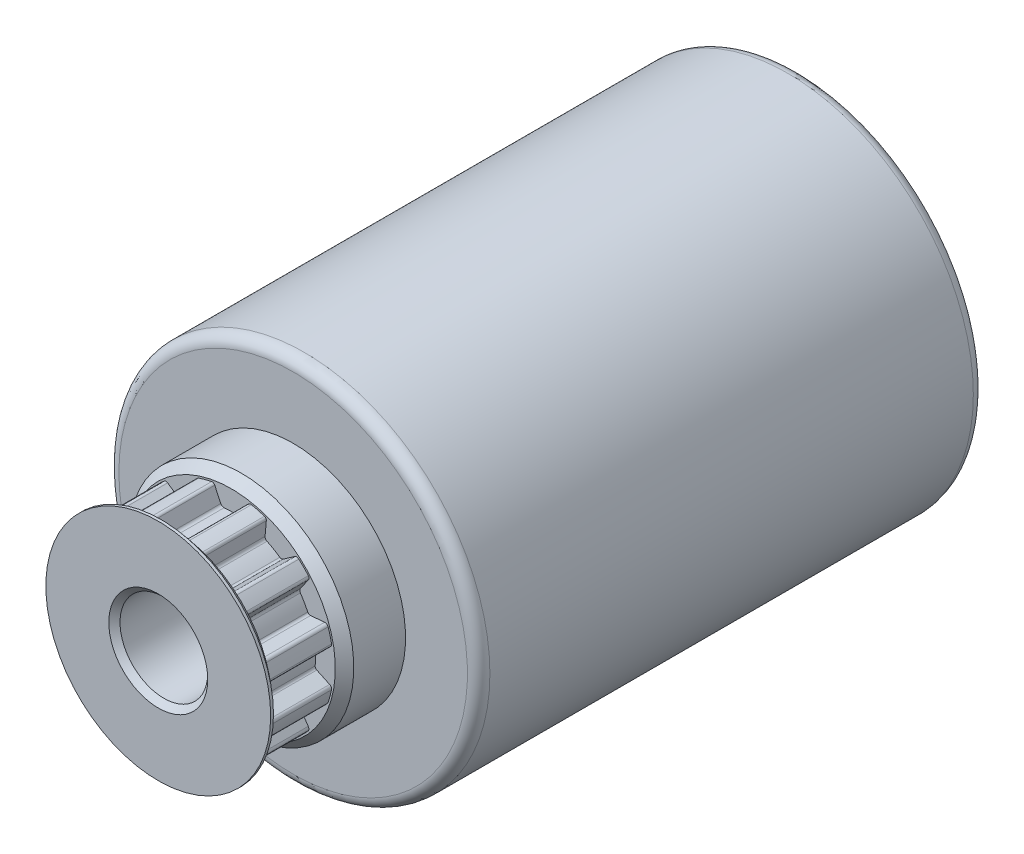
SolidWorks part; units mm, degrees
ref_plane "정면" through (0, 0, 0) normal (0, 0, 1) x (1, 0, 0)
ref_plane "윗면" through (0, 0, 0) normal (0, 1, 0) x (1, 0, 0)
ref_plane "우측면" through (0, 0, 0) normal (1, 0, 0) x (0, 0, -1)
sketch "스케치1" plane through (0, 0, 0) normal (0, 0, 1) x (1, 0, 0)
  line L0 (13.7295, 11.3315) -> (12.2791, 9.2601)
  line L1 (17.5559, 2.9486) -> (15.264, 1.8799)
  line L2 (15.2005, -1.8503) -> (17.4848, -2.9155)
  line L3 (14.0892, 5.9978) -> (16.6, 6.2175)
  line L4 (11.3315, -13.7295) -> (9.2601, -12.2791)
  line L5 (5.9978, -14.0892) -> (6.2175, -16.6)
  line L6 (12.2389, -9.2026) -> (13.6845, -11.2673)
  line L7 (16.6781, -6.2244) -> (14.159, -6.004)
  line L8 (-15.2005, 1.8503) -> (-17.4848, 2.9155)
  line L9 (-17.5559, -2.9486) -> (-15.264, -1.8799)
  line L10 (-16.6781, 6.2244) -> (-14.159, 6.004)
  line L11 (-12.2389, 9.2026) -> (-13.6845, 11.2673)
  line L12 (-14.0892, -5.9978) -> (-16.6, -6.2175)
  line L13 (-13.7295, -11.3315) -> (-12.2791, -9.2601)
  line L14 (-9.2026, -12.2389) -> (-11.2673, -13.6845)
  line L15 (-6.2244, -16.6781) -> (-6.004, -14.159)
  line L16 (-1.8503, -15.2005) -> (-2.9155, -17.4848)
  line L17 (2.9486, -17.5559) -> (1.8799, -15.264)
  line L18 (-5.9978, 14.0892) -> (-6.2175, 16.6)
  line L19 (-11.3315, 13.7295) -> (-9.2601, 12.2791)
  line L20 (9.2026, 12.2389) -> (11.2673, 13.6845)
  line L21 (6.2244, 16.6781) -> (6.004, 14.159)
  line L22 (1.8503, 15.2005) -> (2.9155, 17.4848)
  line L23 (-2.9486, 17.5559) -> (-1.8799, 15.264)
  line L24 (-21, 0) -> (21, 0) construction
  line L25 (0, -21) -> (0, 21) construction
  arc A0 (13.5918, 6.2861) -> (12.2786, 8.5724) centre (0, 0) ccw
  arc A1 (17.8195, -3.5773) -> (17.4848, -2.9155) centre (17.2312, -3.4593) ccw
  arc A2 (15.264, 1.8799) -> (14.9198, 1.2847) centre (15.5176, 1.3361) ccw
  arc A3 (17.5559, 2.9486) -> (17.8352, 3.498) centre (17.3446, 3.4018) ccw
  arc A4 (14.9138, -1.352) -> (15.2005, -1.8503) centre (15.4118, -1.3971) ccw
  arc A5 (14.9138, -1.352) -> (14.9198, 1.2847) centre (0, 0) ccw
  arc A6 (13.5918, 6.2861) -> (14.0892, 5.9978) centre (14.0456, 6.4959) ccw
  arc A7 (9.2601, -12.2791) -> (8.5724, -12.2786) centre (8.9159, -12.7706) ccw
  arc A8 (6.2861, -13.5918) -> (8.5724, -12.2786) centre (0, 0) ccw
  arc A9 (6.2861, -13.5918) -> (5.9978, -14.0892) centre (6.4959, -14.0456) ccw
  arc A10 (11.3315, -13.7295) -> (11.947, -13.6967) centre (11.6183, -13.3199) ccw
  arc A11 (5.8117, -17.2208) -> (6.2175, -16.6) centre (5.6198, -16.6523) ccw
  arc A12 (12.0078, 13.6434) -> (11.2673, 13.6845) centre (11.6114, 13.193) ccw
  arc A13 (13.6434, -12.0078) -> (13.6845, -11.2673) centre (13.193, -11.6114) ccw
  arc A14 (16.6781, -6.2244) -> (17.1947, -5.8882) centre (16.7217, -5.7263) ccw
  arc A15 (14.159, -6.004) -> (13.5632, -6.3474) centre (14.1067, -6.6017) ccw
  arc A16 (12.2398, -8.6278) -> (13.5632, -6.3474) centre (0, 0) ccw
  arc A17 (12.2398, -8.6278) -> (12.2389, -9.2026) centre (12.6484, -8.9159) ccw
  arc A18 (-14.9138, 1.352) -> (-15.2005, 1.8503) centre (-15.4118, 1.3971) ccw
  arc A19 (-14.9138, 1.352) -> (-14.9198, -1.2847) centre (0, 0) ccw
  arc A20 (12.2791, 9.2601) -> (12.2786, 8.5724) centre (12.7706, 8.9159) ccw
  arc A21 (-17.5559, -2.9486) -> (-17.8352, -3.498) centre (-17.3446, -3.4018) ccw
  arc A22 (-16.6781, 6.2244) -> (-17.1947, 5.8882) centre (-16.7217, 5.7263) ccw
  arc A23 (-14.159, 6.004) -> (-13.5632, 6.3474) centre (-14.1067, 6.6017) ccw
  arc A24 (-12.2398, 8.6278) -> (-13.5632, 6.3474) centre (0, 0) ccw
  arc A25 (-12.2398, 8.6278) -> (-12.2389, 9.2026) centre (-12.6484, 8.9159) ccw
  arc A26 (-13.6434, 12.0078) -> (-13.6845, 11.2673) centre (-13.193, 11.6114) ccw
  arc A27 (-17.2208, -5.8117) -> (-16.6, -6.2175) centre (-16.6523, -5.6198) ccw
  arc A28 (17.2208, 5.8117) -> (16.6, 6.2175) centre (16.6523, 5.6198) ccw
  arc A29 (-13.5918, -6.2861) -> (-12.2786, -8.5724) centre (0, 0) ccw
  arc A30 (-12.2791, -9.2601) -> (-12.2786, -8.5724) centre (-12.7706, -8.9159) ccw
  arc A31 (-13.7295, -11.3315) -> (-13.6967, -11.947) centre (-13.3199, -11.6183) ccw
  arc A32 (-13.5918, -6.2861) -> (-14.0892, -5.9978) centre (-14.0456, -6.4959) ccw
  arc A33 (13.7295, 11.3315) -> (13.6967, 11.947) centre (13.3199, 11.6183) ccw
  arc A34 (-12.0078, -13.6434) -> (-11.2673, -13.6845) centre (-11.6114, -13.193) ccw
  arc A35 (-8.6278, -12.2398) -> (-9.2026, -12.2389) centre (-8.9159, -12.6484) ccw
  arc A36 (-8.6278, -12.2398) -> (-6.3474, -13.5632) centre (0, 0) ccw
  arc A37 (-6.004, -14.159) -> (-6.3474, -13.5632) centre (-6.6017, -14.1067) ccw
  arc A38 (-6.2244, -16.6781) -> (-5.8882, -17.1947) centre (-5.7263, -16.7217) ccw
  arc A39 (-3.5773, -17.8195) -> (-2.9155, -17.4848) centre (-3.4593, -17.2312) ccw
  arc A40 (-1.352, -14.9138) -> (-1.8503, -15.2005) centre (-1.3971, -15.4118) ccw
  arc A41 (-1.352, -14.9138) -> (1.2847, -14.9198) centre (0, 0) ccw
  arc A42 (1.8799, -15.264) -> (1.2847, -14.9198) centre (1.3361, -15.5176) ccw
  arc A43 (2.9486, -17.5559) -> (3.498, -17.8352) centre (3.4018, -17.3446) ccw
  arc A44 (-5.8117, 17.2208) -> (-6.2175, 16.6) centre (-5.6198, 16.6523) ccw
  arc A45 (-6.2861, 13.5918) -> (-5.9978, 14.0892) centre (-6.4959, 14.0456) ccw
  arc A46 (-6.2861, 13.5918) -> (-8.5724, 12.2786) centre (0, 0) ccw
  arc A47 (-9.2601, 12.2791) -> (-8.5724, 12.2786) centre (-8.9159, 12.7706) ccw
  arc A48 (-11.3315, 13.7295) -> (-11.947, 13.6967) centre (-11.6183, 13.3199) ccw
  arc A49 (-17.8195, 3.5773) -> (-17.4848, 2.9155) centre (-17.2312, 3.4593) ccw
  arc A50 (-1.8799, 15.264) -> (-1.2847, 14.9198) centre (-1.3361, 15.5176) ccw
  arc A51 (8.6278, 12.2398) -> (9.2026, 12.2389) centre (8.9159, 12.6484) ccw
  arc A52 (8.6278, 12.2398) -> (6.3474, 13.5632) centre (0, 0) ccw
  arc A53 (6.004, 14.159) -> (6.3474, 13.5632) centre (6.6017, 14.1067) ccw
  arc A54 (6.2244, 16.6781) -> (5.8882, 17.1947) centre (5.7263, 16.7217) ccw
  arc A55 (3.5773, 17.8195) -> (2.9155, 17.4848) centre (3.4593, 17.2312) ccw
  arc A56 (-2.9486, 17.5559) -> (-3.498, 17.8352) centre (-3.4018, 17.3446) ccw
  arc A57 (1.352, 14.9138) -> (-1.2847, 14.9198) centre (0, 0) ccw
  arc A58 (1.352, 14.9138) -> (1.8503, 15.2005) centre (1.3971, 15.4118) ccw
  arc A59 (-15.264, -1.8799) -> (-14.9198, -1.2847) centre (-15.5176, -1.3361) ccw
  circle A60 centre (0, 0) radius 18.175
  point P153 (0, 6.5)
  point P154 (0, 6.5)
extrude "보스-돌출1" add sketch "스케치1" along normal mid plane 11 contours A3 A60 A28 L3 A6 A0 A20 L0 A33 A12 L20 A51 A52 A53 L21 A54 A55 L22 A58 A57 A50 L23 A56 A44 L18 A45 A46 A47 L19 A48 A26 L11 A25 A24 A23 L10 A22 A49 L8 A18 A19 A59 L9 A21 A27
sketch "스케치2" plane through (0, 0, 5.5) normal (0, 0, 1) x (1, 0, 0)
  circle A0 centre (0, 0) radius 20
  dimension "D1" = 40
extrude "보스-돌출2" add sketch "스케치2" along normal blind 2
chamfer "모따기1" distance 1.5 angle 50 1 edges at (20, 0, 5.5)
mirror "대칭 복사1" about plane through (0, 0, 0) normal (0, 0, 1) of "모따기1", "보스-돌출2"
sketch "스케치3" plane through (0, 0, -7.5) normal (0, 0, -1) x (-1, 0, 0)
  circle A0 centre (0, 0) radius 3.4
  dimension "D1" = 6.8
extrude "컷-돌출1" cut sketch "스케치3" against normal blind 30
sketch "스케치8" plane through (0, 0, -7.5) normal (0, 0, -1) x (-1, 0, 0)
  circle A0 centre (0, 0) radius 20
  circle A1 centre (0, 0) radius 20 construction
sketch "스케치10" plane through (0, 0, 7.5) normal (0, 0, 1) x (1, 0, 0)
  circle A0 centre (0, 0) radius 7.8
  dimension "D1" = 15.6
extrude "보스-돌출3" add sketch "스케치8" along normal blind 9
sketch "스케치11" plane through (0, 0, -16.5) normal (0, 0, -1) x (-1, 0, 0)
  circle A0 centre (0, 0) radius 33
  dimension "D1" = 66
extrude "보스-돌출4" add sketch "스케치11" along normal blind 90
extrude "컷-돌출2" cut sketch "스케치10" against normal blind 191
chamfer "모따기2" distance 1 angle 45 2 edges at (-7.8, 0, -106.5) (7.8, 0, 7.5)
fillet "필렛1" radius 2 2 edges at (-33, 0, -16.5) (-33, 0, -106.5)
